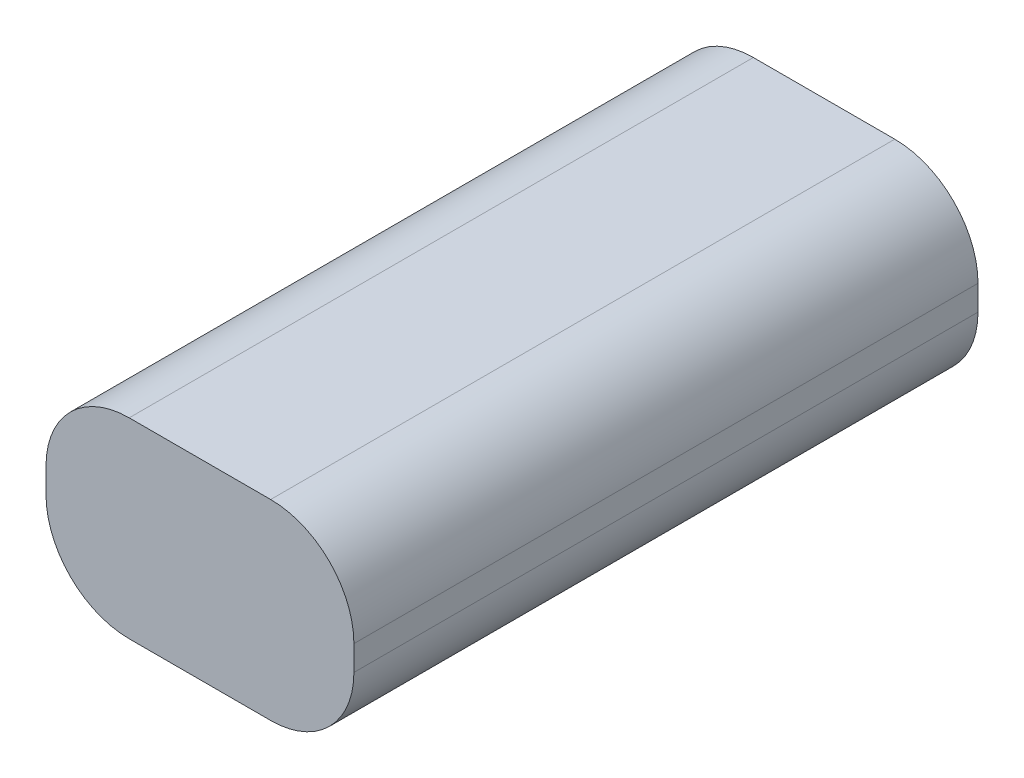
SolidWorks part; units mm, degrees
ref_plane "Front Plane" through (0, 0, 0) normal (0, 0, 1) x (1, 0, 0)
ref_plane "Top Plane" through (0, 0, 0) normal (0, 1, 0) x (1, 0, 0)
ref_plane "Right Plane" through (0, 0, 0) normal (1, 0, 0) x (0, 0, -1)
sketch "Sketch1" plane through (0, 0, 0) normal (0, 1, 0) x (1, 0, 0)
  line L1 (-18.5, 37.5) -> (18.5, 37.5)
  line L2 (-18.5, 37.5) -> (-18.5, -37.5)
  line L3 (-18.5, -37.5) -> (18.5, -37.5)
  line L4 (18.5, 37.5) -> (18.5, -37.5)
  line L5 (-18.5, 37.5) -> (18.5, -37.5) construction
  line L6 (-18.5, -37.5) -> (18.5, 37.5) construction
  point P0 (0, 0)
  dimension "D1" = 75
  dimension "D2" = 37
extrude "Boss-Extrude1" add sketch "Sketch1" along normal blind 23
fillet "Fillet1" radius 10 4 edges at (-18.5, 0, 0) (-18.5, 23, 0) (18.5, 0, 0) (18.5, 23, 0)
